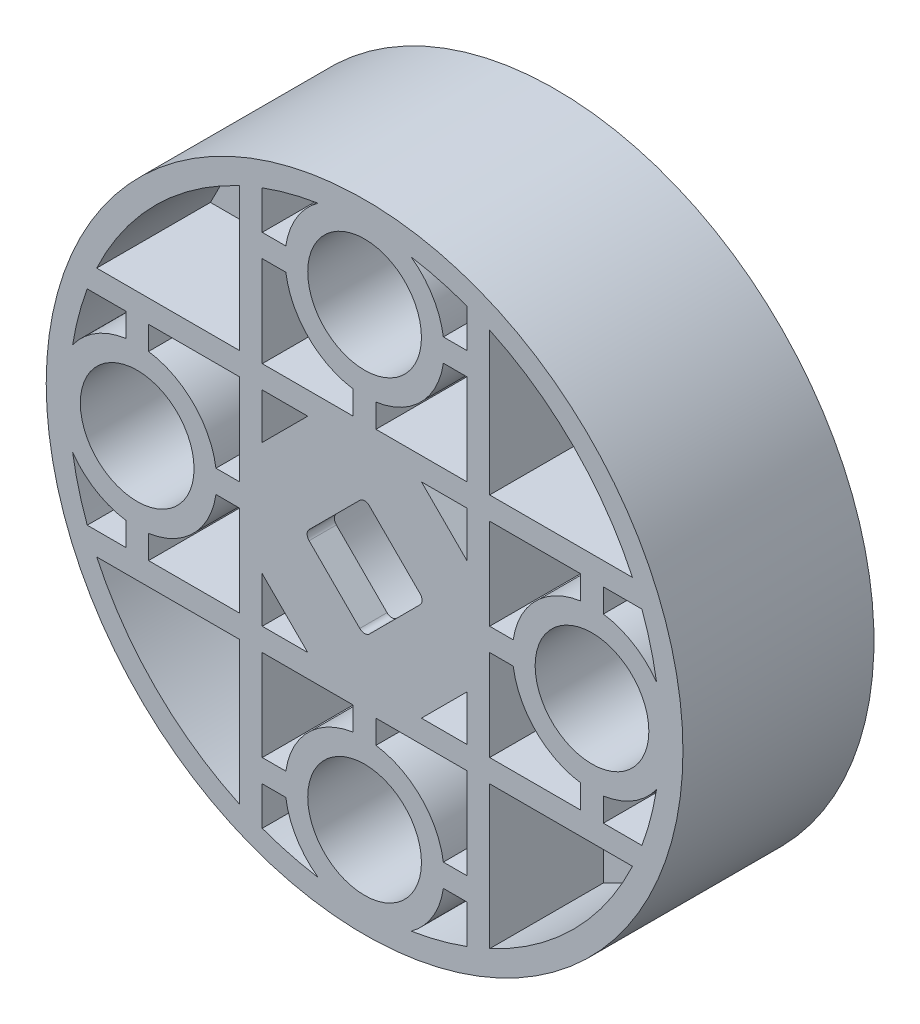
SolidWorks part; units mm, degrees
ref_plane "Front Plane" through (0, 0, 0) normal (0, 0, 1) x (1, 0, 0)
ref_plane "Top Plane" through (0, 0, 0) normal (0, 1, 0) x (1, 0, 0)
ref_plane "Right Plane" through (0, 0, 0) normal (1, 0, 0) x (0, 0, -1)
sketch "Sketch1" plane through (0, 0, 0) normal (0, 0, 1) x (1, 0, 0)
  line L0 (-22.0244, -11.2) -> (5.9756, -11.2) construction
  line L1 (-8.0244, -25.2) -> (-8.0244, 2.8) construction
  circle A0 centre (-8.0244, -11.2) radius 14 construction
  circle A1 centre (-8.0244, -11.2) radius 14
  circle A2 centre (-18.0244, -11.2) radius 2.5 construction
  circle A3 centre (-18.0244, -11.2) radius 2.5
  circle A4 centre (-8.0244, -1.2) radius 2.5 construction
  circle A5 centre (-8.0244, -1.2) radius 2.5
  circle A8 centre (-8.0244, -21.2) radius 2.5 construction
  circle A9 centre (1.9756, -11.2) radius 2.5 construction
  circle A10 centre (-8.0244, -21.2) radius 2.5
  circle A11 centre (1.9756, -11.2) radius 2.5
extrude "Boss-Extrude1" add sketch "Sketch1" along normal up to vertex (9.2 mm away)
sketch "Sketch2" plane through (0, 0, 9.2) normal (0, 0, 1) x (1, 0, 0)
  line L0 (-9.9744, -12.9197) -> (-9.9744, -9.4803)
  line L2 (-6.0744, -12.9197) -> (-6.0744, -9.4803)
  circle A0 centre (-8.0244, -11.2) radius 2.6
  dimension "D1" = 5.2
  dimension "D2" = 3.9
extrude "Cut-Extrude1" cut sketch "Sketch2" against normal through all contours L2 A0 L0
sketch "Sketch3" plane through (0, 0, 9.2) normal (0, 0, 1) x (1, 0, 0)
  line L0 (-12.5244, -23.2) -> (-12.5244, -23.3963)
  line L1 (-20.0244, -6.7) -> (-20.2207, -6.7)
  line L2 (-13.0244, 0.8) -> (-13.0244, -23.2) construction
  line L3 (-3.0244, -23.2) -> (-3.0244, 0.8) construction
  line L4 (-4.0744, -13.5574) -> (-4.0744, -8.8426)
  line L5 (-11.9744, -8.8426) -> (-11.9744, -13.5574)
  line L6 (-4.0744, -13.5574) -> (-4.0744, -8.8426)
  line L7 (-11.9744, -8.8426) -> (-11.9744, -13.5574)
  line L8 (-8.0244, -11.2) -> (-8.0244, 2.8) construction
  line L9 (-13.5244, 0.5792) -> (-13.5244, -22.9792)
  line L10 (-12.5244, 0.9963) -> (-12.5244, -23.2)
  line L11 (-2.5244, -22.9792) -> (-2.5244, 0.5792)
  line L12 (-3.5244, -23.3963) -> (-3.5244, 0.9963)
  line L13 (-3.5244, -23.2) -> (-3.5244, 0.8) construction
  line L14 (-2.5244, -23.2) -> (-2.5244, 0.8) construction
  line L15 (-12.5244, 0.8) -> (-12.5244, -23.2) construction
  line L16 (-13.5244, 0.8) -> (-13.5244, -23.2) construction
  line L17 (4.1719, -6.7) -> (-20.0244, -6.7)
  line L18 (3.7548, -5.7) -> (-19.8036, -5.7)
  line L19 (-20.2207, -15.7) -> (4.1719, -15.7)
  line L20 (-19.8036, -16.7) -> (3.7548, -16.7)
  line L21 (-8.0244, -11.2) -> (-12.5244, -23.2) construction
  line L22 (-8.0244, -11.2) -> (-20.0244, -6.7) construction
  circle A2 centre (-18.0244, -11.2) radius 3.5
  circle A3 centre (-18.0244, -11.2) radius 3.5
  circle A19 centre (-8.0244, -21.2) radius 3.5
  circle A20 centre (-8.0244, -21.2) radius 3.5
  circle A22 centre (1.9756, -11.2) radius 3.5
  circle A23 centre (1.9756, -11.2) radius 3.5
  circle A25 centre (-8.0244, -1.2) radius 3.5
  circle A26 centre (-8.0244, -1.2) radius 3.5
  circle A28 centre (-8.0244, -11.2) radius 13
  circle A29 centre (-8.0244, -11.2) radius 13
  arc A34 (-11.9744, -13.5574) -> (-4.0744, -13.5574) centre (-8.0244, -11.2) ccw
  arc A35 (-4.0744, -8.8426) -> (-11.9744, -8.8426) centre (-8.0244, -11.2) ccw
  arc A36 (-11.9744, -13.5574) -> (-4.0744, -13.5574) centre (-8.0244, -11.2) ccw
  arc A37 (-4.0744, -8.8426) -> (-11.9744, -8.8426) centre (-8.0244, -11.2) ccw
  dimension "D7" = 5
  dimension "D8" = 5
  dimension "D13" = 2
  dimension "D14" = 90
  dimension "D1" = 1
  dimension "D2" = 1
  dimension "D3" = 1
  dimension "D4" = 1
  dimension "D5" = 1
  dimension "D6" = 2
  dimension "D9" = 0.5
  dimension "D10" = 0.5
  dimension "D11" = 0.5
  dimension "D12" = 0.5
extrude "Cut-Extrude2" cut sketch "Sketch3" against normal blind 5 contours L9 A29 L18 | L12 A29 A26 L10 L18 | L1 A29 A3 L19 L9 L17 | A37 L17 L10 L19 A36 L7 | A37 L6 A36 L19 L12 L17 | A23 A29 L17 L11 L19 | L18 A29 L11 | L11 A29 L20 | L0 A29 A20 L12 L20 L10 | L20 A29 L9
sketch "Sketch4" plane through (0, 0, 0) normal (0, 0, -1) x (-1, 0, 0)
  circle A2 centre (8.0244, -11.2) radius 13
  circle A3 centre (8.0244, -11.2) radius 13
  dimension "D1" = 1
extrude "Cut-Extrude3" cut sketch "Sketch4" against normal blind 0.8
sketch "Sketch5" plane through (0, 0, 0.8) normal (0, 0, -1) x (-1, 0, 0)
  line L0 (8.0244, 2.8) -> (8.0244, -25.2) construction
  circle A0 centre (8.0244, -11.2) radius 4.25
  dimension "D1" = 8.5
extrude "Cut-Extrude4" cut sketch "Sketch5" against normal offset from surface (0.7 mm away) 1.5 up to face at (-21.0244, -11.2, 0)
sketch "Sketch6" plane through (0, 0, 0.8) normal (0, 0, -1) x (-1, 0, 0)
  circle A0 centre (8.0244, -11.2) radius 4.25 construction
  circle A1 centre (8.0244, -11.2) radius 4.25
  circle A2 centre (8.0244, -11.2) radius 5.25
  dimension "D1" = 1
extrude "Boss-Extrude2" add sketch "Sketch6" along normal up to surface (0.8 mm away) up to face at (-21.0244, -11.2, 0)
sketch "Sketch7" plane through (0, 0, 0.8) normal (0, 0, -1) x (-1, 0, 0)
  line L0 (7.0705, -15.7) -> (3.5244, -15.7) construction
  line L1 (3.5244, -6.7) -> (7.0705, -6.7) construction
  line L2 (3.5244, -5.7) -> (12.5244, -5.7) construction
  line L3 (12.5244, -16.7) -> (3.5244, -16.7) construction
  line L4 (-3.7548, -5.7) -> (2.5244, -5.7) construction
  line L5 (-4.1719, -6.7) -> (2.5244, -6.7) construction
  line L6 (2.5244, -15.7) -> (-4.1719, -15.7) construction
  line L7 (2.5244, -16.7) -> (-3.7548, -16.7) construction
  line L8 (2.5244, -22.9792) -> (2.5244, -16.7) construction
  line L9 (3.5244, -23.3963) -> (3.5244, -16.7) construction
  line L10 (2.5244, -15.7) -> (2.5244, -6.7) construction
  line L11 (2.5244, -5.7) -> (2.5244, 0.5792) construction
  line L12 (3.5244, -5.7) -> (3.5244, 0.9963) construction
  line L13 (3.5244, -15.7) -> (3.5244, -6.7) construction
  line L14 (12.5244, -16.7) -> (12.5244, -23.3963) construction
  line L15 (12.5244, 0.9963) -> (12.5244, -5.7) construction
  line L16 (12.5244, -6.7) -> (12.5244, -15.7) construction
  line L17 (13.5244, -16.7) -> (13.5244, -22.9792) construction
  line L18 (13.5244, 0.5792) -> (13.5244, -5.7) construction
  line L19 (13.5244, -5.7) -> (19.8036, -5.7) construction
  line L20 (13.5244, -6.7) -> (20.2207, -6.7) construction
  line L21 (13.5244, -6.7) -> (13.5244, -15.7) construction
  line L22 (20.2207, -15.7) -> (13.5244, -15.7) construction
  line L23 (19.8036, -16.7) -> (13.5244, -16.7) construction
  line L24 (12.5244, -15.7) -> (3.5244, -15.7)
  line L25 (3.5244, -6.7) -> (12.5244, -6.7)
  line L26 (3.5244, -5.7) -> (12.5244, -5.7)
  line L27 (12.5244, -16.7) -> (3.5244, -16.7)
  line L28 (-3.7548, -5.7) -> (2.5244, -5.7)
  line L29 (-4.1719, -6.7) -> (2.5244, -6.7)
  line L30 (2.5244, -15.7) -> (-4.1719, -15.7)
  line L31 (2.5244, -16.7) -> (-3.7548, -16.7)
  line L32 (2.5244, -22.9792) -> (2.5244, -16.7)
  line L33 (3.5244, -23.3963) -> (3.5244, -16.7)
  line L34 (2.5244, -15.7) -> (2.5244, -6.7)
  line L35 (2.5244, -5.7) -> (2.5244, 0.5792)
  line L36 (3.5244, -5.7) -> (3.5244, 0.9963)
  line L37 (3.5244, -15.7) -> (3.5244, -6.7)
  line L38 (12.5244, -16.7) -> (12.5244, -23.3963)
  line L39 (12.5244, 0.9963) -> (12.5244, -5.7)
  line L40 (12.5244, -6.7) -> (12.5244, -15.7)
  line L41 (13.5244, -16.7) -> (13.5244, -22.9792)
  line L42 (13.5244, 0.5792) -> (13.5244, -5.7)
  line L43 (13.5244, -5.7) -> (19.8036, -5.7)
  line L44 (13.5244, -6.7) -> (20.2207, -6.7)
  line L45 (13.5244, -6.7) -> (13.5244, -15.7)
  line L46 (20.2207, -15.7) -> (13.5244, -15.7)
  line L47 (19.8036, -16.7) -> (13.5244, -16.7)
  circle A2 centre (18.0244, -11.2) radius 3.5
  circle A3 centre (18.0244, -11.2) radius 3.5
  circle A5 centre (8.0244, -1.2) radius 3.5
  circle A6 centre (8.0244, -1.2) radius 3.5
  circle A8 centre (-1.9756, -11.2) radius 3.5
  circle A9 centre (-1.9756, -11.2) radius 3.5
  circle A10 centre (8.0244, -11.2) radius 13 construction
  circle A11 centre (8.0244, -21.2) radius 3.5
  circle A12 centre (8.0244, -21.2) radius 3.5
  circle A13 centre (8.0244, -11.2) radius 13
  circle A14 centre (8.0244, -11.2) radius 5.25 construction
  circle A15 centre (8.0244, -11.2) radius 5.25
  circle A17 centre (8.0244, -11.2) radius 14
  circle A18 centre (8.0244, -11.2) radius 14
  circle M6 centre (8.0244, -11.2) radius 13
  circle M11 centre (8.0244, -11.2) radius 5.25
  dimension "D1" = 1
  dimension "D2" = 1
  dimension "D3" = 1
  dimension "D4" = 1
  dimension "D5" = 0
extrude "Cut-Extrude5" cut sketch "Sketch7" against normal offset from surface (2.4 mm away) 1 contours L28 L35 M6 | A9 L30 L34 L29 M6 | L32 L31 M6 | A12 L38 L27 L33 M6 | A6 L36 L26 L39 M6 | L42 L43 M6 | A3 L44 L45 L46 M6 | L47 L41 M6 | L40 L24 M11 | L40 L25 M11 | L37 L25 M11 | L37 L24 M11 up to face at (-0.2471, -18.9773, 4.2)
chamfer "Chamfer1" distance 0.6 angle 45 4 edges at (-6.0744, -11.2, 1.5) (-8.0244, -8.6, 1.5) (-8.0244, -13.8, 1.5) (-9.9744, -11.2, 1.5)
sketch "Sketch8" plane through (0, 0, 9.2) normal (0, 0, 1) x (1, 0, 0)
  line L0 (-11.9744, -8.8426) -> (-11.9744, -13.5574) construction
  line L1 (-11.9744, -8.8426) -> (-11.9744, -13.5574)
  line L2 (-4.0744, -13.5574) -> (-4.0744, -8.8426) construction
  line L3 (-4.0744, -13.5574) -> (-4.0744, -8.8426)
  line L4 (-8.0244, -7.1341) -> (-12.0903, -11.2)
  line L5 (-3.9586, -11.2) -> (-8.0244, -7.1341)
  line L6 (-8.0244, -15.2659) -> (-3.9586, -11.2)
  line L7 (-12.0903, -11.2) -> (-8.0244, -15.2659)
  line L8 (-8.0244, -7.1341) -> (-12.0903, -11.2)
  line L9 (-3.9586, -11.2) -> (-8.0244, -7.1341)
  line L10 (-8.0244, -15.2659) -> (-3.9586, -11.2)
  line L11 (-12.0903, -11.2) -> (-8.0244, -15.2659)
  line L12 (-8.0244, -13.8517) -> (-5.3728, -11.2)
  line L13 (-10.6761, -11.2) -> (-8.0244, -13.8517)
  line L14 (-8.0244, -8.5483) -> (-10.6761, -11.2)
  line L15 (-5.3728, -11.2) -> (-8.0244, -8.5483)
  line L16 (-8.0244, -13.8517) -> (-5.3728, -11.2)
  line L17 (-10.6761, -11.2) -> (-8.0244, -13.8517)
  line L18 (-8.0244, -8.5483) -> (-10.6761, -11.2)
  line L19 (-5.3728, -11.2) -> (-8.0244, -8.5483)
  line L20 (-3.5244, -6.7) -> (-12.5244, -6.7)
  line L21 (-3.5244, -15.7) -> (-3.5244, -6.7)
  line L22 (-12.5244, -15.7) -> (-3.5244, -15.7)
  line L23 (-12.5244, -6.7) -> (-12.5244, -15.7)
  line L24 (-3.5244, -6.7) -> (-12.5244, -6.7)
  line L25 (-3.5244, -15.7) -> (-3.5244, -6.7)
  line L26 (-12.5244, -15.7) -> (-3.5244, -15.7)
  line L27 (-12.5244, -6.7) -> (-12.5244, -15.7)
  dimension "D1" = 0
  dimension "D2" = 0
  dimension "D3" = 0
extrude "Cut-Extrude6" cut sketch "Sketch8" against normal up to surface (5 mm away)
sketch "Sketch9" plane through (0, 0, 9.2) normal (0, 0, 1) x (1, 0, 0)
  line L0 (-4.0744, -13.5574) -> (-4.0744, -8.8426) construction
  line L1 (-11.9744, -8.8426) -> (-11.9744, -13.5574) construction
  line L2 (-4.0744, -13.5574) -> (-4.0744, -8.8426)
  line L3 (-11.9744, -8.8426) -> (-11.9744, -13.5574)
  line L4 (-3.5244, -6.7) -> (-12.5244, -6.7)
  line L5 (-12.5244, -6.7) -> (-12.5244, -15.7)
  line L6 (-12.5244, -15.7) -> (-3.5244, -15.7)
  line L7 (-3.5244, -15.7) -> (-3.5244, -6.7)
  line L8 (-3.5244, -6.7) -> (-12.5244, -6.7)
  line L9 (-12.5244, -6.7) -> (-12.5244, -15.7)
  line L10 (-12.5244, -15.7) -> (-3.5244, -15.7)
  line L11 (-3.5244, -15.7) -> (-3.5244, -6.7)
  line L12 (-8.0244, -13.8517) -> (-5.3728, -11.2)
  line L13 (-5.3728, -11.2) -> (-8.0244, -8.5483)
  line L14 (-8.0244, -8.5483) -> (-10.6761, -11.2)
  line L15 (-10.6761, -11.2) -> (-8.0244, -13.8517)
  line L16 (-8.0244, -13.8517) -> (-5.3728, -11.2)
  line L17 (-5.3728, -11.2) -> (-8.0244, -8.5483)
  line L18 (-8.0244, -8.5483) -> (-10.6761, -11.2)
  line L19 (-10.6761, -11.2) -> (-8.0244, -13.8517)
  line L20 (-8.0244, -7.1341) -> (-12.0903, -11.2)
  line L21 (-12.0903, -11.2) -> (-8.0244, -15.2659)
  line L22 (-8.0244, -15.2659) -> (-3.9586, -11.2)
  line L23 (-3.9586, -11.2) -> (-8.0244, -7.1341)
  line L24 (-8.0244, -7.1341) -> (-12.0903, -11.2)
  line L25 (-12.0903, -11.2) -> (-8.0244, -15.2659)
  line L26 (-8.0244, -15.2659) -> (-3.9586, -11.2)
  line L27 (-3.9586, -11.2) -> (-8.0244, -7.1341)
  line M18 (-11.9744, -11.0841) -> (-11.9744, -11.3159)
  line M21 (-4.0744, -11.3159) -> (-4.0744, -11.0841)
  dimension "D1" = 0
  dimension "D2" = 0
  dimension "D3" = 0
extrude "Boss-Extrude3" add sketch "Sketch9" against normal up to surface (5 mm away) contours L24 L25 M18 | L26 L27 M21
sketch "Sketch10" plane through (0, 0, 9.2) normal (0, 0, 1) x (1, 0, 0)
  line L4 (-8.0244, -7.1341) -> (-12.0903, -11.2)
  line L5 (-12.0903, -11.2) -> (-8.0244, -15.2659)
  line L6 (-8.0244, -15.2659) -> (-3.9586, -11.2)
  line L7 (-3.9586, -11.2) -> (-8.0244, -7.1341)
  line L8 (-8.0244, -7.1341) -> (-12.0903, -11.2)
  line L9 (-12.0903, -11.2) -> (-8.0244, -15.2659)
  line L10 (-8.0244, -15.2659) -> (-3.9586, -11.2)
  line L11 (-3.9586, -11.2) -> (-8.0244, -7.1341)
  dimension "D1" = 0
extrude "Boss-Extrude4" add sketch "Sketch10" against normal up to surface (0.2 mm away)
sketch "Sketch11" plane through (0, 0, 9.2) normal (0, 0, 1) x (1, 0, 0)
  line L0 (-11.9744, -8.8426) -> (-11.9744, -13.5574) construction
  line L1 (-4.0744, -13.5574) -> (-4.0744, -8.8426) construction
  line L2 (-11.9744, -8.8426) -> (-11.9744, -13.5574)
  line L3 (-4.0744, -13.5574) -> (-4.0744, -8.8426)
  line L4 (-8.0244, -7.1341) -> (-12.0903, -11.2)
  line L5 (-12.0903, -11.2) -> (-8.0244, -15.2659)
  line L6 (-8.0244, -15.2659) -> (-3.9586, -11.2)
  line L7 (-3.9586, -11.2) -> (-8.0244, -7.1341)
  line L8 (-8.0244, -7.1341) -> (-12.0903, -11.2)
  line L9 (-12.0903, -11.2) -> (-8.0244, -15.2659)
  line L10 (-8.0244, -15.2659) -> (-3.9586, -11.2)
  line L11 (-3.9586, -11.2) -> (-8.0244, -7.1341)
  line L12 (-8.0244, -13.8517) -> (-5.3728, -11.2)
  line L13 (-5.3728, -11.2) -> (-8.0244, -8.5483)
  line L14 (-8.0244, -8.5483) -> (-10.6761, -11.2)
  line L15 (-10.6761, -11.2) -> (-8.0244, -13.8517)
  line L16 (-8.0244, -13.8517) -> (-5.3728, -11.2)
  line L17 (-5.3728, -11.2) -> (-8.0244, -8.5483)
  line L18 (-8.0244, -8.5483) -> (-10.6761, -11.2)
  line L19 (-10.6761, -11.2) -> (-8.0244, -13.8517)
  line L20 (-3.5244, -6.7) -> (-12.5244, -6.7)
  line L21 (-12.5244, -6.7) -> (-12.5244, -15.7)
  line L22 (-12.5244, -15.7) -> (-3.5244, -15.7)
  line L23 (-3.5244, -15.7) -> (-3.5244, -6.7)
  line L24 (-3.5244, -6.7) -> (-12.5244, -6.7)
  line L25 (-12.5244, -6.7) -> (-12.5244, -15.7)
  line L26 (-12.5244, -15.7) -> (-3.5244, -15.7)
  line L27 (-3.5244, -15.7) -> (-3.5244, -6.7)
  dimension "D1" = 0
  dimension "D2" = 0
  dimension "D3" = 0
extrude "Cut-Extrude7" cut sketch "Sketch11" against normal up to surface (0.2 mm away) contours L18 L19 L16 L17 up to face at (-8.0244, -11.2, 9)
fillet "Fillet1" [suppressed] radius 0.2
sketch "Sketch12" plane through (0, 0, 9.2) normal (0, 0, 1) x (1, 0, 0)
  line L4 (-12.0903, -11.2) -> (-8.0244, -15.2659)
  line L5 (-8.0244, -7.1341) -> (-12.0903, -11.2)
  line L6 (-3.9586, -11.2) -> (-8.0244, -7.1341)
  line L7 (-8.0244, -15.2659) -> (-3.9586, -11.2)
  line L8 (-12.0903, -11.2) -> (-8.0244, -15.2659)
  line L9 (-8.0244, -7.1341) -> (-12.0903, -11.2)
  line L10 (-3.9586, -11.2) -> (-8.0244, -7.1341)
  line L11 (-8.0244, -15.2659) -> (-3.9586, -11.2)
  line L12 (-13.1509, -11.2) -> (-8.0244, -16.3265)
  line L13 (-8.0244, -6.0735) -> (-13.1509, -11.2)
  line L14 (-2.8979, -11.2) -> (-8.0244, -6.0735)
  line L15 (-8.0244, -16.3265) -> (-2.8979, -11.2)
  line L16 (-13.1509, -11.2) -> (-8.0244, -16.3265)
  line L17 (-8.0244, -6.0735) -> (-13.1509, -11.2)
  line L18 (-2.8979, -11.2) -> (-8.0244, -6.0735)
  line L19 (-8.0244, -16.3265) -> (-2.8979, -11.2)
  dimension "D1" = 0
  dimension "D2" = 0
extrude "Boss-Extrude5" [suppressed] add sketch "Sketch12" against normal up to surface (5 mm away)
sketch "Sketch13" plane through (0, 0, 9.2) normal (0, 0, 1) x (1, 0, 0)
  line L0 (-20.2207, -15.7) -> (-13.5244, -15.7) construction
  line L1 (-13.5244, -6.7) -> (-13.5244, -15.7) construction
  line L2 (-13.5244, -6.7) -> (-20.2207, -6.7) construction
  line L3 (-12.5244, 0.9963) -> (-12.5244, -5.7) construction
  line L4 (-3.5244, -5.7) -> (-12.5244, -5.7) construction
  line L5 (-3.5244, -5.7) -> (-3.5244, 0.9963) construction
  line L6 (-3.5244, -1.7) -> (-12.5244, -1.7) construction
  line L7 (-8.5244, -1.2) -> (-8.5244, -21.2) construction
  line L8 (-7.5244, -1.2) -> (-7.5244, -21.2) construction
  line L9 (-3.5244, -0.7) -> (-12.5244, -0.7) construction
  line L10 (-3.5244, -20.7) -> (-12.5244, -20.7) construction
  line L11 (-3.5244, -21.7) -> (-12.5244, -21.7) construction
  line L12 (-3.5244, -16.7) -> (-3.5244, -23.3963) construction
  line L13 (-12.5244, -16.7) -> (-3.5244, -16.7) construction
  line L14 (-12.5244, -23.3963) -> (-12.5244, -16.7) construction
  line L15 (-2.5244, -6.7) -> (4.1719, -6.7) construction
  line L16 (-2.5244, -15.7) -> (-2.5244, -6.7) construction
  line L17 (-18.0244, -11.7) -> (1.9756, -11.7) construction
  line L18 (-18.0244, -10.7) -> (1.9756, -10.7) construction
  line L19 (1.4756, -6.7) -> (1.4756, -15.7) construction
  line L20 (2.4756, -6.7) -> (2.4756, -15.7) construction
  line L21 (4.1719, -15.7) -> (-2.5244, -15.7) construction
  line L22 (-18.5244, -6.7) -> (-18.5244, -15.7) construction
  line L23 (-17.5244, -6.7) -> (-17.5244, -15.7) construction
  line L24 (-20.2207, -15.7) -> (-13.5244, -15.7)
  line L25 (-13.5244, -6.7) -> (-13.5244, -15.7)
  line L26 (-13.5244, -6.7) -> (-20.2207, -6.7)
  line L27 (-12.5244, 0.9963) -> (-12.5244, -5.7)
  line L28 (-3.5244, -5.7) -> (-12.5244, -5.7)
  line L29 (-3.5244, -5.7) -> (-3.5244, 0.9963)
  line L30 (-3.5244, -1.7) -> (-12.5244, -1.7)
  line L31 (-8.5244, -1.2) -> (-8.5244, -21.2)
  line L32 (-7.5244, -1.2) -> (-7.5244, -21.2)
  line L33 (-3.5244, -0.7) -> (-12.5244, -0.7)
  line L34 (-3.5244, -20.7) -> (-12.5244, -20.7)
  line L35 (-3.5244, -21.7) -> (-12.5244, -21.7)
  line L36 (-3.5244, -16.7) -> (-3.5244, -23.3963)
  line L37 (-12.5244, -16.7) -> (-3.5244, -16.7)
  line L38 (-12.5244, -23.3963) -> (-12.5244, -16.7)
  line L39 (-2.5244, -6.7) -> (4.1719, -6.7)
  line L40 (-2.5244, -15.7) -> (-2.5244, -6.7)
  line L41 (-18.0244, -11.7) -> (1.9756, -11.7)
  line L42 (-18.0244, -10.7) -> (1.9756, -10.7)
  line L43 (1.4756, -6.7) -> (1.4756, -15.7)
  line L44 (2.4756, -6.7) -> (2.4756, -15.7)
  line L45 (4.1719, -15.7) -> (-2.5244, -15.7)
  line L46 (-18.5244, -6.7) -> (-18.5244, -15.7)
  line L47 (-17.5244, -6.7) -> (-17.5244, -15.7)
  line L48 (-12.5244, -6.7) -> (-12.5244, -15.7) construction
  line L49 (-3.5244, -15.7) -> (-3.5244, -6.7) construction
  line L50 (-8.0244, -15.2659) -> (-3.9586, -11.2) construction
  line L51 (-8.0244, -15.2659) -> (-12.0903, -11.2) construction
  line L52 (-12.0903, -11.2) -> (-8.0244, -7.1341) construction
  line L53 (-8.0244, -7.1341) -> (-3.9586, -11.2) construction
  line L54 (-12.5244, -6.7) -> (-12.5244, -15.7)
  line L55 (-3.5244, -15.7) -> (-3.5244, -6.7)
  line L56 (-8.0244, -15.2659) -> (-3.9586, -11.2)
  line L57 (-8.0244, -15.2659) -> (-12.0903, -11.2)
  line L58 (-12.0903, -11.2) -> (-8.0244, -7.1341)
  line L59 (-8.0244, -7.1341) -> (-3.9586, -11.2)
  arc A0 (-5.9754, -24.0375) -> (-10.0735, -24.0375) centre (-8.0244, -21.2) ccw construction
  arc A1 (4.8131, -9.151) -> (4.8131, -13.249) centre (1.9756, -11.2) ccw construction
  arc A2 (-20.8619, -13.249) -> (-20.8619, -9.151) centre (-18.0244, -11.2) ccw construction
  arc A3 (-10.0735, 1.6375) -> (-5.9754, 1.6375) centre (-8.0244, -1.2) ccw construction
  arc A4 (-5.9754, -24.0375) -> (-10.0735, -24.0375) centre (-8.0244, -21.2) ccw
  arc A5 (4.8131, -9.151) -> (4.8131, -13.249) centre (1.9756, -11.2) ccw
  arc A6 (-20.8619, -13.249) -> (-20.8619, -9.151) centre (-18.0244, -11.2) ccw
  arc A7 (-10.0735, 1.6375) -> (-5.9754, 1.6375) centre (-8.0244, -1.2) ccw
  line M61 (-12.5244, -6.7) -> (-3.5244, -6.7)
  line M62 (-3.5244, -6.7) -> (-3.5244, -15.7)
  line M63 (-3.5244, -15.7) -> (-12.5244, -15.7)
  line M64 (-12.5244, -15.7) -> (-12.5244, -6.7)
extrude "Boss-Extrude6" add sketch "Sketch13" against normal up to surface (5 mm away) contours A4 L34 L38 L35 | A4 L32 L37 L31 | A4 L35 L36 L34 | A5 L43 L45 L44 | A5 L42 L40 L41 | A5 L44 L39 L43 | A7 L30 L29 L33 | A7 L31 L28 L32 | A7 L33 L27 L30 | A6 L41 L25 L42 | A6 L47 L26 L46 | A6 L46 L24 L47 | L57 L58 L42 L41 M64 | L42 L59 L56 L41 M62 | L56 L57 L31 L32 M63 | L58 L59 L32 L31 M61 up to face at (-8.0244, -20.3416, 4.2)
sketch "Sketch14" plane through (0, 0, 0.8) normal (0, 0, -1) x (-1, 0, 0)
  circle A0 centre (8.0244, -11.2) radius 18.4031
extrude "Cut-Extrude8" cut sketch "Sketch14" along normal blind 14
sketch "Sketch15" plane through (0, 0, 0.8) normal (0, 0, -1) x (-1, 0, 0)
  line L1 (3.5244, -6.7) -> (12.5244, -6.7)
  line L2 (3.5244, -6.7) -> (3.5244, -15.7)
  line L3 (3.5244, -15.7) -> (12.5244, -15.7)
  line L4 (12.5244, -6.7) -> (12.5244, -15.7)
extrude "Cut-Extrude9" cut sketch "Sketch15" against normal up to surface (2.4 mm away) up to face at (1.1172, -11.2, 3.2)
sketch "Sketch18" plane through (0, 0, 9.2) normal (0, 0, 1) x (1, 0, 0)
  line L5 (-8.0244, -8.5483) -> (-10.6761, -11.2)
  line L6 (-5.3728, -11.2) -> (-8.0244, -8.5483)
  line L7 (-8.0244, -13.8517) -> (-5.3728, -11.2)
  line L8 (-10.6761, -11.2) -> (-8.0244, -13.8517)
  line L9 (-8.0244, -8.5483) -> (-10.6761, -11.2)
  line L10 (-5.3728, -11.2) -> (-8.0244, -8.5483)
  line L11 (-8.0244, -13.8517) -> (-5.3728, -11.2)
  line L12 (-10.6761, -11.2) -> (-8.0244, -13.8517)
  dimension "D1" = 0
extrude "Cut-Extrude10" cut sketch "Sketch18" against normal through all
sketch "Sketch19" plane through (0, 0, 3.2) normal (0, 0, -1) x (-1, 0, 0)
  line L1 (9.9744, -10.4983) -> (8.0766, -8.6005) construction
  line L2 (6.0744, -10.4983) -> (7.9722, -8.6005)
  line L3 (6.0744, -9.4803) -> (6.0744, -10.4983)
  line L4 (6.0744, -10.4983) -> (7.9722, -8.6005)
  line L5 (6.0744, -9.4803) -> (6.0744, -10.4983)
  line L6 (8.0766, -13.7995) -> (9.9744, -11.9017) construction
  line L7 (7.9722, -13.7995) -> (6.0744, -11.9017)
  line L8 (6.0744, -11.9017) -> (6.0744, -12.9197)
  line L9 (7.9722, -13.7995) -> (6.0744, -11.9017)
  line L10 (6.0744, -11.9017) -> (6.0744, -12.9197)
  line L11 (9.9744, -10.4983) -> (8.0766, -8.6005)
  line L12 (8.0766, -13.7995) -> (9.9744, -11.9017)
  line L16 (10.6761, -11.2) -> (9.9744, -10.4983)
  line L17 (9.9744, -11.9017) -> (10.6761, -11.2)
  line L18 (9.9744, -12.9197) -> (9.9744, -11.9017)
  line L19 (8.0244, -13.8517) -> (8.0766, -13.7995)
  line L20 (7.9722, -13.7995) -> (8.0244, -13.8517)
  line L21 (6.0744, -11.9017) -> (6.0744, -12.9197)
  line L22 (5.3728, -11.2) -> (6.0744, -11.9017)
  line L23 (6.0744, -10.4983) -> (5.3728, -11.2)
  line L24 (6.0744, -9.4803) -> (6.0744, -10.4983)
  line L25 (8.0244, -8.5483) -> (7.9722, -8.6005)
  line L26 (8.0766, -8.6005) -> (8.0244, -8.5483)
  line L27 (9.9744, -10.4983) -> (9.9744, -9.4803)
  line L28 (10.6761, -11.2) -> (9.9744, -10.4983)
  line L29 (9.9744, -11.9017) -> (10.6761, -11.2)
  line L30 (9.9744, -12.9197) -> (9.9744, -11.9017)
  line L31 (8.0244, -13.8517) -> (8.0766, -13.7995)
  line L32 (7.9722, -13.7995) -> (8.0244, -13.8517)
  line L33 (6.0744, -11.9017) -> (6.0744, -12.9197)
  line L34 (5.3728, -11.2) -> (6.0744, -11.9017)
  line L35 (6.0744, -10.4983) -> (5.3728, -11.2)
  line L36 (6.0744, -9.4803) -> (6.0744, -10.4983)
  line L37 (8.0244, -8.5483) -> (7.9722, -8.6005)
  line L38 (8.0766, -8.6005) -> (8.0244, -8.5483)
  line L39 (9.9744, -10.4983) -> (9.9744, -9.4803)
  arc A1 (7.9722, -8.6005) -> (6.0744, -9.4803) centre (8.0244, -11.2) ccw
  arc A2 (7.9722, -8.6005) -> (6.0744, -9.4803) centre (8.0244, -11.2) ccw
  arc A4 (6.0744, -12.9197) -> (7.9722, -13.7995) centre (8.0244, -11.2) ccw
  arc A5 (6.0744, -12.9197) -> (7.9722, -13.7995) centre (8.0244, -11.2) ccw
  arc A7 (8.0766, -13.7995) -> (9.9744, -12.9197) centre (8.0244, -11.2) ccw
  arc A8 (6.0744, -12.9197) -> (7.9722, -13.7995) centre (8.0244, -11.2) ccw
  arc A9 (7.9722, -8.6005) -> (6.0744, -9.4803) centre (8.0244, -11.2) ccw
  arc A10 (9.9744, -9.4803) -> (8.0766, -8.6005) centre (8.0244, -11.2) ccw
  arc A11 (8.0766, -13.7995) -> (9.9744, -12.9197) centre (8.0244, -11.2) ccw
  arc A12 (6.0744, -12.9197) -> (7.9722, -13.7995) centre (8.0244, -11.2) ccw
  arc A13 (7.9722, -8.6005) -> (6.0744, -9.4803) centre (8.0244, -11.2) ccw
  arc A14 (9.9744, -9.4803) -> (8.0766, -8.6005) centre (8.0244, -11.2) ccw
  line M29 (9.9744, -11.9017) -> (9.9744, -12.9197)
  arc M30 (9.9744, -12.9197) -> (8.0766, -13.7995) centre (8.0244, -11.2) cw
  arc M33 (7.9722, -13.7995) -> (6.0744, -12.9197) centre (8.0244, -11.2) cw
  line M34 (6.0744, -12.9197) -> (6.0744, -11.9017)
  line M37 (6.0744, -10.4983) -> (6.0744, -9.4803)
  arc M38 (6.0744, -9.4803) -> (7.9722, -8.6005) centre (8.0244, -11.2) cw
  arc M41 (8.0766, -8.6005) -> (9.9744, -9.4803) centre (8.0244, -11.2) cw
  line M42 (9.9744, -9.4803) -> (9.9744, -10.4983)
  dimension "D1" = 0
  dimension "D2" = 0
  dimension "D3" = 0
extrude "Boss-Extrude7" add sketch "Sketch19" against normal up to surface (5.8 mm away) contours L4 M37 M38 | L11 M42 M41 | L9 M33 M34 | L12 M30 M29 up to face at (-6.6762, -12.94, 9)
sketch "Sketch20" plane through (0, 0, 3.2) normal (0, 0, -1) x (-1, 0, 0)
  line L0 (3.5244, -15.7) -> (3.5244, -6.7) construction
  line L1 (12.5244, -6.7) -> (12.5244, -15.7) construction
  line L2 (8.5244, -1.2) -> (8.5244, -21.2) construction
  line L3 (3.5244, -1.7) -> (12.5244, -1.7) construction
  line L4 (12.0903, -11.2) -> (8.0244, -7.1341)
  line L5 (8.0244, -7.1341) -> (3.9586, -11.2)
  line L6 (3.9586, -11.2) -> (8.0244, -15.2659)
  line L7 (8.0244, -15.2659) -> (12.0903, -11.2)
  line L8 (12.0903, -11.2) -> (8.0244, -7.1341)
  line L9 (8.0244, -7.1341) -> (3.9586, -11.2)
  line L10 (3.9586, -11.2) -> (8.0244, -15.2659)
  line L11 (8.0244, -15.2659) -> (12.0903, -11.2)
  line L12 (12.5244, 0.9963) -> (12.5244, -5.7) construction
  line L13 (3.5244, -5.7) -> (12.5244, -5.7) construction
  line L14 (3.5244, -5.7) -> (3.5244, 0.9963) construction
  line L15 (20.2207, -15.7) -> (13.5244, -15.7) construction
  line L16 (13.5244, -6.7) -> (13.5244, -15.7) construction
  line L17 (13.5244, -6.7) -> (20.2207, -6.7) construction
  line L18 (3.5244, -16.7) -> (3.5244, -23.3963) construction
  line L19 (12.5244, -16.7) -> (3.5244, -16.7) construction
  line L20 (12.5244, -23.3963) -> (12.5244, -16.7) construction
  line L21 (3.5244, -21.7) -> (12.5244, -21.7) construction
  line L22 (3.5244, -20.7) -> (12.5244, -20.7) construction
  line L23 (3.5244, -0.7) -> (12.5244, -0.7) construction
  line L24 (7.5244, -1.2) -> (7.5244, -21.2) construction
  line L25 (18.0244, -11.7) -> (-1.9756, -11.7) construction
  line L26 (2.5244, -6.7) -> (-4.1719, -6.7) construction
  line L27 (2.5244, -15.7) -> (2.5244, -6.7) construction
  line L28 (-4.1719, -15.7) -> (2.5244, -15.7) construction
  line L29 (17.5244, -6.7) -> (17.5244, -15.7) construction
  line L30 (18.5244, -6.7) -> (18.5244, -15.7) construction
  line L31 (-2.4756, -6.7) -> (-2.4756, -15.7) construction
  line L32 (-1.4756, -6.7) -> (-1.4756, -15.7) construction
  line L33 (18.0244, -10.7) -> (-1.9756, -10.7) construction
  line L34 (3.5244, -15.7) -> (3.5244, -6.7)
  line L35 (12.5244, -6.7) -> (12.5244, -15.7)
  line L36 (8.5244, -1.2) -> (8.5244, -21.2)
  line L37 (3.5244, -1.7) -> (12.5244, -1.7)
  line L38 (12.5244, 0.9963) -> (12.5244, -5.7)
  line L39 (3.5244, -5.7) -> (12.5244, -5.7)
  line L40 (3.5244, -5.7) -> (3.5244, 0.9963)
  line L41 (20.2207, -15.7) -> (13.5244, -15.7)
  line L42 (13.5244, -6.7) -> (13.5244, -15.7)
  line L43 (13.5244, -6.7) -> (20.2207, -6.7)
  line L44 (3.5244, -16.7) -> (3.5244, -23.3963)
  line L45 (12.5244, -16.7) -> (3.5244, -16.7)
  line L46 (12.5244, -23.3963) -> (12.5244, -16.7)
  line L47 (3.5244, -21.7) -> (12.5244, -21.7)
  line L48 (3.5244, -20.7) -> (12.5244, -20.7)
  line L49 (3.5244, -0.7) -> (12.5244, -0.7)
  line L50 (7.5244, -1.2) -> (7.5244, -21.2)
  line L51 (18.0244, -11.7) -> (-1.9756, -11.7)
  line L52 (2.5244, -6.7) -> (-4.1719, -6.7)
  line L53 (2.5244, -15.7) -> (2.5244, -6.7)
  line L54 (-4.1719, -15.7) -> (2.5244, -15.7)
  line L55 (17.5244, -6.7) -> (17.5244, -15.7)
  line L56 (18.5244, -6.7) -> (18.5244, -15.7)
  line L57 (-2.4756, -6.7) -> (-2.4756, -15.7)
  line L58 (-1.4756, -6.7) -> (-1.4756, -15.7)
  line L59 (18.0244, -10.7) -> (-1.9756, -10.7)
  line L64 (10.6761, -11.2) -> (8.0244, -8.5483)
  line L65 (8.0244, -13.8517) -> (10.6761, -11.2)
  line L66 (5.3728, -11.2) -> (8.0244, -13.8517)
  line L67 (8.0244, -8.5483) -> (5.3728, -11.2)
  line L68 (10.6761, -11.2) -> (8.0244, -8.5483)
  line L69 (8.0244, -13.8517) -> (10.6761, -11.2)
  line L70 (5.3728, -11.2) -> (8.0244, -13.8517)
  line L71 (8.0244, -8.5483) -> (5.3728, -11.2)
  arc A0 (10.0735, -24.0375) -> (5.9754, -24.0375) centre (8.0244, -21.2) ccw construction
  arc A1 (5.9754, 1.6375) -> (10.0735, 1.6375) centre (8.0244, -1.2) ccw construction
  arc A2 (20.8619, -9.151) -> (20.8619, -13.249) centre (18.0244, -11.2) ccw construction
  arc A3 (-4.8131, -13.249) -> (-4.8131, -9.151) centre (-1.9756, -11.2) ccw construction
  arc A4 (10.0735, -24.0375) -> (5.9754, -24.0375) centre (8.0244, -21.2) ccw
  arc A5 (5.9754, 1.6375) -> (10.0735, 1.6375) centre (8.0244, -1.2) ccw
  arc A6 (20.8619, -9.151) -> (20.8619, -13.249) centre (18.0244, -11.2) ccw
  arc A7 (-4.8131, -13.249) -> (-4.8131, -9.151) centre (-1.9756, -11.2) ccw
  line M9 (8.0244, -8.5483) -> (10.6761, -11.2)
  line M10 (10.6761, -11.2) -> (8.0244, -13.8517)
  line M11 (8.0244, -13.8517) -> (5.3728, -11.2)
  line M12 (5.3728, -11.2) -> (8.0244, -8.5483)
  line M14 (12.5244, -6.7) -> (3.5244, -6.7)
  line M16 (3.5244, -15.7) -> (12.5244, -15.7)
  dimension "D1" = 0
  dimension "D2" = 0
extrude "Boss-Extrude8" add sketch "Sketch20" along normal up to surface (2.4 mm away) contours A7 L58 L52 L57 | A7 L57 L54 L58 | A7 L51 L53 L59 | L9 L59 L34 L51 L10 | L59 L9 L10 L51 M12 M11 | L51 L10 L50 M11 | L50 L10 L11 L36 M11 M10 | L11 L51 L36 M10 | L8 L59 L51 L11 M9 M10 | L59 L8 L36 M9 | L9 L50 L36 L8 M12 M9 | L59 L50 L9 M12 | L35 L59 L8 L11 L51 | L10 L50 L36 L11 M16 | L50 L9 L8 L36 M14 | A5 L50 L39 L36 | A5 L37 L38 L49 | A5 L49 L40 L37 | A6 L59 L42 L51 | A6 L56 L43 L55 | A6 L55 L41 L56 | A4 L36 L45 L50 | A4 L47 L46 L48 | A4 L48 L44 L47 up to face at (-8.0244, -11.2, 0.8)
fillet "Fillet2" radius 0.3 4 edges at (-5.3728, -11.2, 5) (-8.0244, -13.8517, 5) (-10.6761, -11.2, 5) (-8.0244, -8.5483, 5)
sketch "Sketch21" plane through (0, 0, 0.8) normal (0, 0, -1) x (-1, 0, 0)
  line L2 (12.0166, -10.9495) -> (8.2749, -7.2079)
  line L3 (4.0323, -11.4505) -> (7.7739, -15.1921)
  line L4 (12.0166, -10.9495) -> (8.2749, -7.2079)
  line L5 (4.0323, -11.4505) -> (7.7739, -15.1921)
  arc A2 (8.2749, -7.2079) -> (4.0323, -11.4505) centre (8.0244, -11.2) ccw
  arc A3 (7.7739, -15.1921) -> (12.0166, -10.9495) centre (8.0244, -11.2) ccw
  arc A4 (8.2749, -7.2079) -> (4.0323, -11.4505) centre (8.0244, -11.2) ccw
  arc A5 (7.7739, -15.1921) -> (12.0166, -10.9495) centre (8.0244, -11.2) ccw
  dimension "D1" = 0
extrude "Cut-Extrude11" cut sketch "Sketch21" against normal offset from surface (7.2 mm away) 1.2
sketch "Sketch22" plane through (0, 0, 0.8) normal (0, 0, -1) x (-1, 0, 0)
  line L0 (3.0747, -11.9071) -> (7.3173, -16.1497)
  line L1 (12.9742, -10.4929) -> (8.7315, -6.2503)
  line L2 (12.0166, -10.9495) -> (8.2749, -7.2079)
  line L3 (4.0323, -11.4505) -> (7.7739, -15.1921)
  line L4 (12.0166, -10.9495) -> (8.2749, -7.2079)
  line L5 (4.0323, -11.4505) -> (7.7739, -15.1921)
  arc A0 (8.7315, -6.2503) -> (3.0747, -11.9071) centre (8.0244, -11.2) ccw
  arc A1 (7.3173, -16.1497) -> (12.9742, -10.4929) centre (8.0244, -11.2) ccw
  arc A2 (8.2749, -7.2079) -> (4.0323, -11.4505) centre (8.0244, -11.2) ccw
  arc A3 (7.7739, -15.1921) -> (12.0166, -10.9495) centre (8.0244, -11.2) ccw
  arc A4 (8.2749, -7.2079) -> (4.0323, -11.4505) centre (8.0244, -11.2) ccw
  arc A5 (7.7739, -15.1921) -> (12.0166, -10.9495) centre (8.0244, -11.2) ccw
  dimension "D1" = 0
  dimension "D2" = 1
extrude "Boss-Extrude9" add sketch "Sketch22" against normal up to vertex
sketch "Sketch23" plane through (0, 0, 9.2) normal (0, 0, 1) x (1, 0, 0)
  line L0 (-12.5244, -10.7) -> (-11.5903, -10.7) construction
  line L1 (-12.5244, -6.7) -> (-12.5244, -10.7) construction
  line L2 (-12.5244, -10.0431) -> (-9.1813, -6.7) construction
  line L3 (-8.5244, -6.7) -> (-12.5244, -6.7) construction
  line L4 (-8.5244, -6.7) -> (-8.5244, -7.6341) construction
  line L5 (-8.5244, -7.6341) -> (-11.5903, -10.7) construction
  line L6 (-12.5244, -10.7) -> (-11.5903, -10.7)
  line L7 (-12.5244, -10.0431) -> (-12.5244, -10.7)
  line L8 (-12.5244, -10.0431) -> (-9.1813, -6.7) construction
  line L9 (-8.5244, -6.7) -> (-9.1813, -6.7)
  line L10 (-8.5244, -6.7) -> (-8.5244, -7.6341)
  line L11 (-8.5244, -7.6341) -> (-11.5903, -10.7)
  line L12 (-4.4586, -10.7) -> (-3.5244, -10.7) construction
  line L13 (-3.5244, -10.7) -> (-3.5244, -6.7) construction
  line L14 (-3.5244, -6.7) -> (-7.5244, -6.7) construction
  line L15 (-7.5244, -6.7) -> (-7.5244, -7.6341) construction
  line L16 (-4.4586, -10.7) -> (-7.5244, -7.6341) construction
  line L17 (-4.4586, -10.7) -> (-3.5244, -10.7)
  line L18 (-3.5244, -10.7) -> (-3.5244, -9.0206)
  line L19 (-5.845, -6.7) -> (-7.5244, -6.7)
  line L20 (-7.5244, -6.7) -> (-7.5244, -7.6341)
  line L21 (-4.4586, -10.7) -> (-7.5244, -7.6341)
  line L22 (-7.5244, -15.7) -> (-3.5244, -15.7) construction
  line L23 (-7.5244, -14.7659) -> (-7.5244, -15.7) construction
  line L24 (-7.5244, -14.7659) -> (-4.4586, -11.7) construction
  line L25 (-4.4586, -11.7) -> (-3.5244, -11.7) construction
  line L27 (-3.5244, -12.3569) -> (-6.8676, -15.7) construction
  line L28 (-7.5244, -15.7) -> (-6.8676, -15.7)
  line L29 (-7.5244, -14.7659) -> (-7.5244, -15.7)
  line L30 (-7.5244, -14.7659) -> (-4.4586, -11.7)
  line L31 (-4.4586, -11.7) -> (-3.5244, -11.7)
  line L33 (-3.5244, -12.3569) -> (-6.8676, -15.7) construction
  line L34 (-12.5244, -15.7) -> (-8.5244, -15.7) construction
  line L35 (-8.5244, -14.7659) -> (-8.5244, -15.7) construction
  line L36 (-11.5903, -11.7) -> (-8.5244, -14.7659) construction
  line L37 (-12.5244, -11.7) -> (-11.5903, -11.7) construction
  line L38 (-12.5244, -11.7) -> (-12.5244, -15.7) construction
  line L39 (-10.2039, -15.7) -> (-8.5244, -15.7)
  line L40 (-8.5244, -14.7659) -> (-8.5244, -15.7)
  line L41 (-11.5903, -11.7) -> (-8.5244, -14.7659)
  line L42 (-12.5244, -11.7) -> (-11.5903, -11.7)
  line L43 (-12.5244, -11.7) -> (-12.5244, -13.3794)
  line L44 (-3.5244, -12.3569) -> (-3.5244, -11.7)
  line L45 (-3.5244, -15.7) -> (-3.5244, -11.7) construction
  line L46 (-3.5244, -6.7) -> (-7.5244, -6.7)
  line L47 (-3.5244, -10.7) -> (-3.5244, -6.7)
  line L48 (-3.5244, -15.7) -> (-3.5244, -11.7)
  line L49 (-7.5244, -15.7) -> (-3.5244, -15.7)
  line L50 (-12.5244, -15.7) -> (-8.5244, -15.7)
  line L51 (-12.5244, -11.7) -> (-12.5244, -15.7)
  line L52 (-12.5244, -6.7) -> (-12.5244, -10.7)
  line L53 (-8.5244, -6.7) -> (-12.5244, -6.7)
  line L54 (-12.5244, -13.7) -> (-10.5244, -15.7)
  line L55 (-10.5244, -6.7) -> (-12.5244, -8.7)
  line L56 (-3.5244, -8.7) -> (-5.5244, -6.7)
  line L57 (-5.5244, -15.7) -> (-3.5244, -13.7)
  arc A0 (-3.5244, -9.0206) -> (-5.845, -6.7) centre (-8.0244, -11.2) ccw construction
  arc A1 (-3.5244, -9.0206) -> (-5.845, -6.7) centre (-8.0244, -11.2) ccw construction
  arc A2 (-12.5244, -13.3794) -> (-10.2039, -15.7) centre (-8.0244, -11.2) ccw construction
  arc A3 (-12.5244, -13.3794) -> (-10.2039, -15.7) centre (-8.0244, -11.2) ccw construction
  point P42 (-8.0244, -11.2)
  dimension "D1" = 2
  dimension "D2" = 4
extrude "Boss-Extrude10" add sketch "Sketch23" against normal up to surface (5 mm away) contours L53 L55 L52 L7 L6 L11 L10 L9 | L51 L54 L50 L39 L40 L41 L42 L43 | L49 L57 L48 L44 L31 L30 L29 L28 | L47 L56 L46 L19 L20 L21 L17 L18
sketch "Sketch24" plane through (0, 0, 9.2) normal (0, 0, 1) x (1, 0, 0)
  line L0 (-3.5244, -8.7) -> (-5.5244, -6.7) construction
  line L1 (-4.0244, -8.2) -> (-5.0244, -7.2)
  line L2 (-12.5244, -13.7) -> (-10.5244, -15.7) construction
  line L3 (-12.0244, -14.2) -> (-11.0244, -15.2)
  arc A0 (-4.0244, -8.2) -> (-5.0244, -7.2) centre (-8.0244, -11.2) ccw construction
  arc A1 (-4.0244, -8.2) -> (-5.0244, -7.2) centre (-8.0244, -11.2) ccw
  arc A2 (-12.0244, -14.2) -> (-11.0244, -15.2) centre (-8.0244, -11.2) ccw construction
  arc A3 (-12.0244, -14.2) -> (-11.0244, -15.2) centre (-8.0244, -11.2) ccw
extrude "Cut-Extrude13" cut sketch "Sketch24" against normal up to surface (5 mm away)
sketch "Sketch25" plane through (0, 0, 0.8) normal (0, 0, -1) x (-1, 0, 0)
  line L3 (12.0166, -10.9495) -> (8.2749, -7.2079)
  line L4 (4.0323, -11.4505) -> (7.7739, -15.1921)
  line L5 (12.0166, -10.9495) -> (8.2749, -7.2079)
  line L6 (4.0323, -11.4505) -> (7.7739, -15.1921)
  arc A2 (8.2749, -7.2079) -> (4.0323, -11.4505) centre (8.0244, -11.2) ccw
  arc A3 (7.7739, -15.1921) -> (12.0166, -10.9495) centre (8.0244, -11.2) ccw
  arc A4 (8.2749, -7.2079) -> (4.0323, -11.4505) centre (8.0244, -11.2) ccw
  arc A5 (7.7739, -15.1921) -> (12.0166, -10.9495) centre (8.0244, -11.2) ccw
  dimension "D1" = 0
extrude "Cut-Extrude14" cut sketch "Sketch25" against normal up to surface (7.2 mm away)
